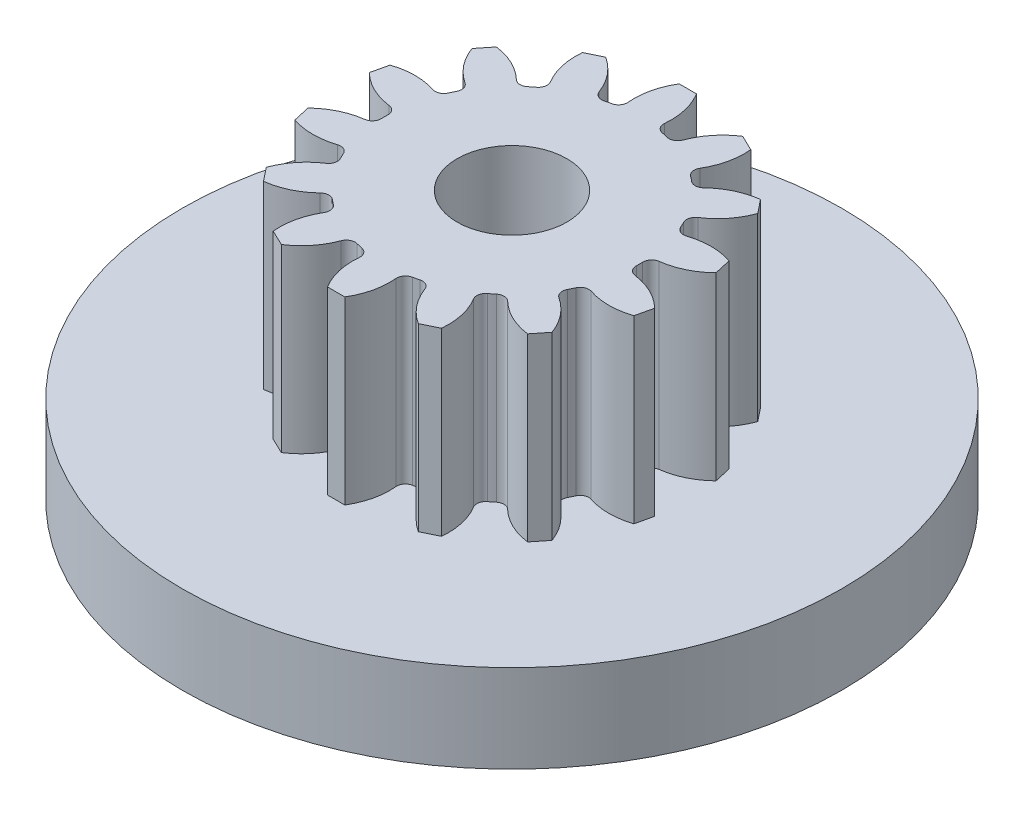
SolidWorks part; units mm, degrees
ref_plane "Front Plane" through (0, 0, 0) normal (0, 0, 1) x (1, 0, 0)
ref_plane "Top Plane" through (0, 0, 0) normal (0, 1, 0) x (1, 0, 0)
ref_plane "Right Plane" through (0, 0, 0) normal (1, 0, 0) x (0, 0, -1)
sketch "Sketch1" plane through (0, 0, 0) normal (0, 1, 0) x (1, 0, 0)
  line L0 (0, 0) -> (0, 4) construction
  line L1 (-0.197, 4) -> (0.197, 4)
  line L4 (1.558, 3.6894) -> (1.913, 3.5184)
  line L5 (3.0045, 2.648) -> (3.2502, 2.3399)
  line L6 (3.8559, 1.0821) -> (3.9435, 0.698)
  line L7 (3.9435, -0.698) -> (3.8559, -1.0821)
  line L8 (3.2502, -2.3399) -> (3.0045, -2.648)
  line L9 (1.913, -3.5184) -> (1.558, -3.6894)
  line L10 (0.197, -4) -> (-0.197, -4)
  line L11 (-1.558, -3.6894) -> (-1.913, -3.5184)
  line L12 (-3.0045, -2.648) -> (-3.2502, -2.3399)
  line L13 (-3.8559, -1.0821) -> (-3.9435, -0.698)
  line L14 (-3.9435, 0.698) -> (-3.8559, 1.0821)
  line L15 (-3.2502, 2.3399) -> (-3.0045, 2.648)
  line L16 (-1.913, 3.5184) -> (-1.558, 3.6894)
  arc A0 (-1.7513, 2.3115) -> (-1.8638, 2.2217) centre (0, 0) ccw
  circle A1 centre (0, 0) radius 3.5 construction
  arc A3 (-0.197, 4) -> (-0.4155, 3.0571) centre (1.1119, 3.2) ccw
  arc A4 (0.197, 4) -> (0.4155, 3.0571) centre (-1.1119, 3.2) cw
  arc A5 (-0.5749, 2.8424) -> (-0.4155, 3.0571) centre (-0.6146, 3.0385) ccw
  arc A6 (0.5749, 2.8424) -> (0.4155, 3.0571) centre (0.6146, 3.0385) cw
  arc A7 (0.7153, 2.8104) -> (0.9521, 2.9346) centre (0.7646, 3.0042) ccw
  arc A8 (1.558, 3.6894) -> (0.9521, 2.9346) centre (2.3902, 2.4007) ccw
  arc A9 (1.913, 3.5184) -> (1.7007, 2.5741) centre (0.3866, 3.3655) cw
  arc A10 (1.7513, 2.3115) -> (1.7007, 2.5741) centre (1.8721, 2.4709) cw
  arc A11 (1.8638, 2.2217) -> (2.1311, 2.2309) centre (1.9924, 2.375) ccw
  arc A12 (3.0045, 2.648) -> (2.1311, 2.2309) centre (3.1951, 1.1258) ccw
  arc A13 (3.2502, 2.3399) -> (2.6492, 1.5813) centre (1.8086, 2.8645) cw
  arc A14 (2.5808, 1.3227) -> (2.6492, 1.5813) centre (2.7588, 1.414) cw
  arc A15 (2.6432, 1.193) -> (2.888, 1.0853) centre (2.8255, 1.2753) ccw
  arc A16 (3.8559, 1.0821) -> (2.888, 1.0853) centre (3.3672, -0.372) ccw
  arc A17 (3.9435, 0.698) -> (3.0729, 0.2752) centre (2.8723, 1.7961) cw
  arc A18 (2.8991, 0.072) -> (3.0729, 0.2752) centre (3.099, 0.077) cw
  arc A19 (2.8991, -0.072) -> (3.0729, -0.2752) centre (3.099, -0.077) ccw
  arc A20 (3.9435, -0.698) -> (3.0729, -0.2752) centre (2.8723, -1.7961) ccw
  arc A21 (3.8559, -1.0821) -> (2.888, -1.0853) centre (3.3672, 0.372) cw
  arc A22 (2.6432, -1.193) -> (2.888, -1.0853) centre (2.8255, -1.2753) cw
  arc A23 (2.5808, -1.3227) -> (2.6492, -1.5813) centre (2.7588, -1.414) ccw
  arc A24 (3.2502, -2.3399) -> (2.6492, -1.5813) centre (1.8086, -2.8645) ccw
  arc A25 (3.0045, -2.648) -> (2.1311, -2.2309) centre (3.1951, -1.1258) cw
  arc A26 (1.8638, -2.2217) -> (2.1311, -2.2309) centre (1.9924, -2.375) cw
  arc A27 (1.7513, -2.3115) -> (1.7007, -2.5741) centre (1.8721, -2.4709) ccw
  arc A28 (1.913, -3.5184) -> (1.7007, -2.5741) centre (0.3866, -3.3655) ccw
  arc A29 (1.558, -3.6894) -> (0.9521, -2.9346) centre (2.3902, -2.4007) cw
  arc A30 (0.7153, -2.8104) -> (0.9521, -2.9346) centre (0.7646, -3.0042) cw
  arc A31 (0.5749, -2.8424) -> (0.4155, -3.0571) centre (0.6146, -3.0385) ccw
  arc A32 (0.197, -4) -> (0.4155, -3.0571) centre (-1.1119, -3.2) ccw
  arc A33 (-0.197, -4) -> (-0.4155, -3.0571) centre (1.1119, -3.2) cw
  arc A34 (-0.5749, -2.8424) -> (-0.4155, -3.0571) centre (-0.6146, -3.0385) cw
  arc A35 (-0.7153, -2.8104) -> (-0.9521, -2.9346) centre (-0.7646, -3.0042) ccw
  arc A36 (-1.558, -3.6894) -> (-0.9521, -2.9346) centre (-2.3902, -2.4007) ccw
  arc A37 (-1.913, -3.5184) -> (-1.7007, -2.5741) centre (-0.3866, -3.3655) cw
  arc A38 (-1.7513, -2.3115) -> (-1.7007, -2.5741) centre (-1.8721, -2.4709) cw
  arc A39 (-1.8638, -2.2217) -> (-2.1311, -2.2309) centre (-1.9924, -2.375) ccw
  arc A40 (-3.0045, -2.648) -> (-2.1311, -2.2309) centre (-3.1951, -1.1258) ccw
  arc A41 (-3.2502, -2.3399) -> (-2.6492, -1.5813) centre (-1.8086, -2.8645) cw
  arc A42 (-2.5808, -1.3227) -> (-2.6492, -1.5813) centre (-2.7588, -1.414) cw
  arc A43 (-2.6432, -1.193) -> (-2.888, -1.0853) centre (-2.8255, -1.2753) ccw
  arc A44 (-3.8559, -1.0821) -> (-2.888, -1.0853) centre (-3.3672, 0.372) ccw
  arc A45 (-3.9435, -0.698) -> (-3.0729, -0.2752) centre (-2.8723, -1.7961) cw
  arc A46 (-2.8991, -0.072) -> (-3.0729, -0.2752) centre (-3.099, -0.077) cw
  arc A47 (-2.8991, 0.072) -> (-3.0729, 0.2752) centre (-3.099, 0.077) ccw
  arc A48 (-3.9435, 0.698) -> (-3.0729, 0.2752) centre (-2.8723, 1.7961) ccw
  arc A49 (-3.8559, 1.0821) -> (-2.888, 1.0853) centre (-3.3672, -0.372) cw
  arc A50 (-2.6432, 1.193) -> (-2.888, 1.0853) centre (-2.8255, 1.2753) cw
  arc A51 (-2.5808, 1.3227) -> (-2.6492, 1.5813) centre (-2.7588, 1.414) ccw
  arc A52 (-3.2502, 2.3399) -> (-2.6492, 1.5813) centre (-1.8086, 2.8645) ccw
  arc A53 (-3.0045, 2.648) -> (-2.1311, 2.2309) centre (-3.1951, 1.1258) cw
  arc A54 (-1.8638, 2.2217) -> (-2.1311, 2.2309) centre (-1.9924, 2.375) cw
  arc A55 (-1.7513, 2.3115) -> (-1.7007, 2.5741) centre (-1.8721, 2.4709) ccw
  arc A56 (-1.913, 3.5184) -> (-1.7007, 2.5741) centre (-0.3866, 3.3655) ccw
  arc A57 (-1.558, 3.6894) -> (-0.9521, 2.9346) centre (-2.3902, 2.4007) cw
  arc A58 (-0.7153, 2.8104) -> (-0.9521, 2.9346) centre (-0.7646, 3.0042) cw
  arc A59 (-2.5808, 1.3227) -> (-2.6432, 1.193) centre (0, 0) ccw
  arc A60 (-2.8991, 0.072) -> (-2.8991, -0.072) centre (0, 0) ccw
  arc A61 (-2.6432, -1.193) -> (-2.5808, -1.3227) centre (0, 0) ccw
  arc A62 (-1.8638, -2.2217) -> (-1.7513, -2.3115) centre (0, 0) ccw
  arc A63 (-0.7153, -2.8104) -> (-0.5749, -2.8424) centre (0, 0) ccw
  arc A64 (0.5749, -2.8424) -> (0.7153, -2.8104) centre (0, 0) ccw
  arc A65 (1.7513, -2.3115) -> (1.8638, -2.2217) centre (0, 0) ccw
  arc A66 (2.5808, -1.3227) -> (2.6432, -1.193) centre (0, 0) ccw
  arc A67 (2.8991, -0.072) -> (2.8991, 0.072) centre (0, 0) ccw
  arc A68 (2.6432, 1.193) -> (2.5808, 1.3227) centre (0, 0) ccw
  arc A69 (1.8638, 2.2217) -> (1.7513, 2.3115) centre (0, 0) ccw
  arc A70 (0.7153, 2.8104) -> (0.5749, 2.8424) centre (0, 0) ccw
  arc A71 (-0.7153, 2.8104) -> (-0.5749, 2.8424) centre (0, 0) cw
  circle A72 centre (0, 0) radius 1.25
  point P9 (0, 4)
  point P13 (0, 3.5)
  point P14 (0, 2.9)
  dimension "D1" = 7
  dimension "D2" = 2.5
  dimension "D3" = 5.8
  dimension "D6" = 0.2
  dimension "D7" = 0.2
  dimension "D4" = 0.394
  dimension "D8" = 14
extrude "Boss-Extrude1" add sketch "Sketch1" along normal blind 4.1
sketch "Sketch2" plane through (0, 0, 0) normal (0, -1, 0) x (1, 0, 0)
  circle A0 centre (0, 0) radius 7.5
  circle A1 centre (0, 0) radius 1.25
  dimension "D1" = 15
  dimension "D2" = 2.5
extrude "Boss-Extrude2" add sketch "Sketch2" along normal blind 2
